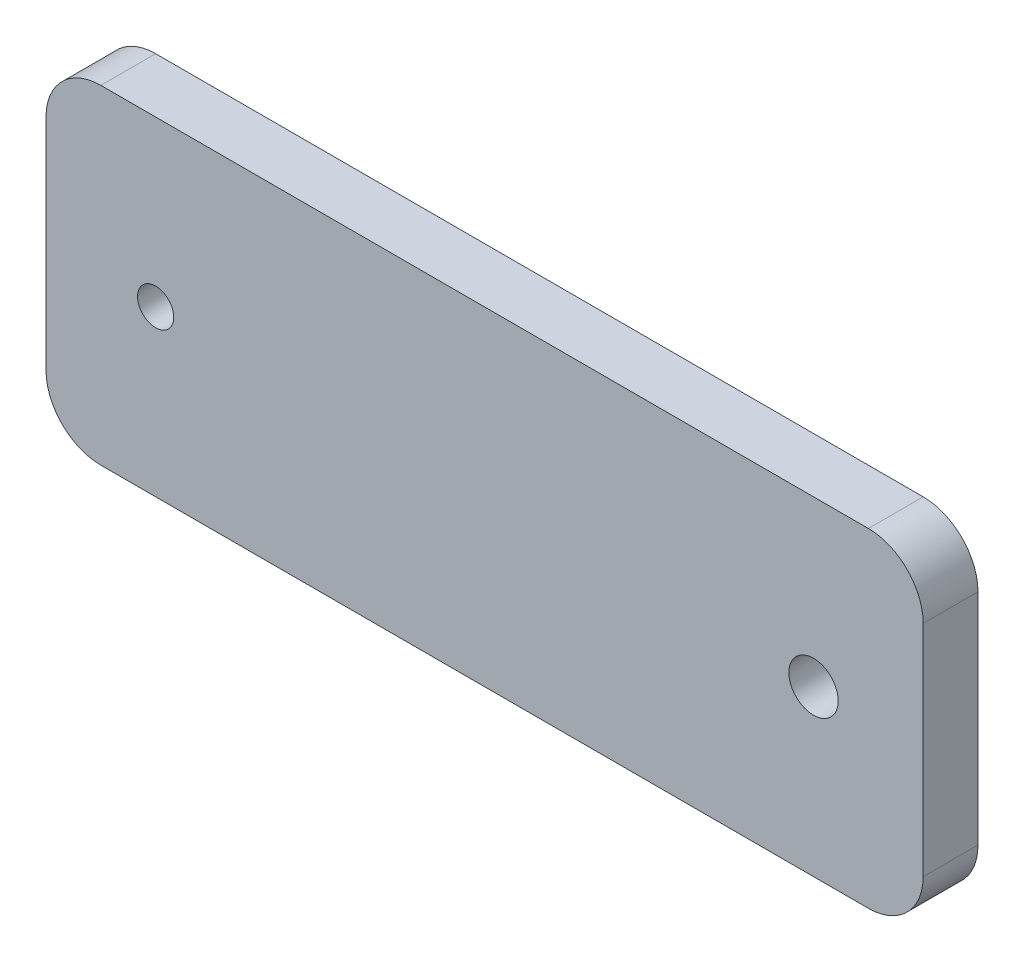
SolidWorks part; units mm, degrees
material "AISI 1020"
ref_plane "Face" through (0, 0, 0) normal (0, 0, 1) x (1, 0, 0)
ref_plane "Dessus" through (0, 0, 0) normal (0, 1, 0) x (1, 0, 0)
ref_plane "Droite" through (0, 0, 0) normal (1, 0, 0) x (0, 0, -1)
sketch "Esquisse1" plane through (0, 0, 0) normal (0, 0, 1) x (1, 0, 0)
  line L1 (-35, 15) -> (35, 15)
  line L2 (-40, 10) -> (-40, -10)
  line L3 (-35, -15) -> (35, -15)
  line L4 (40, 10) -> (40, -10)
  arc A0 (35, -15) -> (40, -10) centre (35, -10) ccw
  arc A1 (40, 10) -> (35, 15) centre (35, 10) ccw
  arc A2 (-35, -15) -> (-40, -10) centre (-35, -10) cw
  arc A3 (-40, 10) -> (-35, 15) centre (-35, 10) cw
  circle A5 centre (30, 0) radius 2.25
  point P7 (40, -15)
  point P12 (-40, -15)
  point P15 (-40, 15)
  dimension "D5" = 5
  dimension "D7" = 4.5
  dimension "D1" = 40
  dimension "D2" = 80
  dimension "D3" = 15
  dimension "D4" = 30
extrude "Boss.-Extru.1" add sketch "Esquisse1" along normal blind 5
hole_wizard "Trou taraudé M41" positions "Esquisse3" profile "Esquisse2" tap size "M4" standard "Iso" end condition up to next
sketch "Esquisse3" plane through (0, 0, 5) normal (0, 0, 1) x (1, 0, 0)
  point P0 (-30, 0)
  dimension "D1" = 30
sketch "Esquisse2" plane through (-30, 0, 5) normal (1, 0, 0) x (0, -1, 0)
  line L0 (0, 0) -> (0, 5)
  line L1 (0, 5) -> (1.65, 5)
  line L2 (1.65, 5) -> (1.65, 0)
  line L5 (1.65, 0) -> (0, 0)
  line L11 (0, -6.35) -> (0, 107.95) construction
  dimension "Diamètre du trou pour taraudage jusqu'au prochain" = 3.3
  dimension "Profondeur du trou pour taraudage jusqu'au prochain" = 5
cosmetic thread "Filetage de perçage1" parameters "D2"=4
